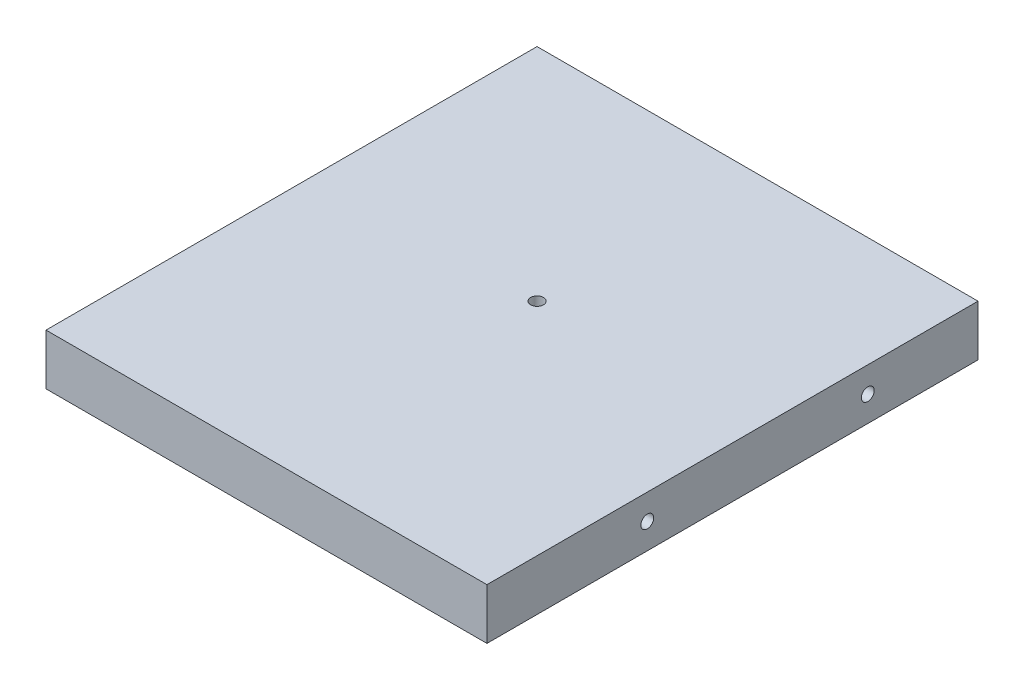
SolidWorks part; units mm, degrees
ref_plane "Front Plane" through (0, 0, 0) normal (0, 0, 1) x (1, 0, 0)
ref_plane "Top Plane" through (0, 0, 0) normal (0, 1, 0) x (1, 0, 0)
ref_plane "Right Plane" through (0, 0, 0) normal (1, 0, 0) x (0, 0, -1)
sketch "Sketch4" plane through (0, 0, 0) normal (0, 1, 0) x (1, 0, 0)
  line L1 (61.7729, 131.481) -> (281.7729, 131.481)
  line L2 (61.7729, 131.481) -> (61.7729, -88.519)
  line L3 (61.7729, -88.519) -> (281.7729, -88.519)
  line L4 (281.7729, 131.481) -> (281.7729, -88.519)
  dimension "D1" = 220
extrude "Boss-Extrude2" add sketch "Sketch4" along normal blind 25.4
sketch "Sketch5" plane through (0, 25.4, 0) normal (0, 1, 0) x (1, 0, 0)
  circle A0 centre (171.7729, 21.481) radius 3.2
extrude "Cut-Extrude1" cut sketch "Sketch5" against normal blind 25.4
sketch "Sketch6" plane through (281.7729, 0, 0) normal (1, 0, 0) x (0, 0, -1)
  circle A0 centre (-33.519, 12.7) radius 3.2
  circle A1 centre (76.481, 12.7) radius 3.2
sketch "Sketch7" plane through (61.7729, 0, 0) normal (-1, 0, 0) x (0, 0, 1)
  circle A0 centre (-76.481, 12.7) radius 3.2
  circle A1 centre (33.519, 12.7) radius 3.2
extrude "Cut-Extrude2" cut sketch "Sketch7" against normal blind 30
extrude "Cut-Extrude4" cut sketch "Sketch6" against normal blind 30
sketch "Sketch13" plane through (0, 0, 88.519) normal (0, 0, 1) x (1, 0, 0)
  line L1 (61.7729, 25.4) -> (281.7729, 25.4)
  line L2 (61.7729, 25.4) -> (61.7729, 0)
  line L3 (61.7729, 0) -> (281.7729, 0)
  line L4 (281.7729, 25.4) -> (281.7729, 0)
  dimension "D1" = 25.4
  dimension "D2" = 220
extrude "Boss-Extrude3" add sketch "Sketch13" along normal blind 25
